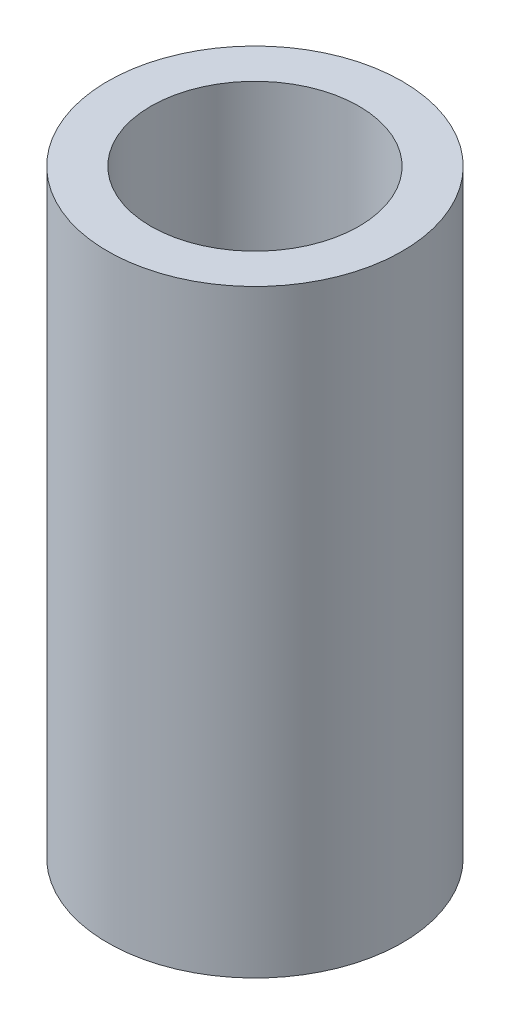
SolidWorks part; units mm, degrees
ref_plane "Front Plane" through (0, 0, 0) normal (0, 0, 1) x (1, 0, 0)
ref_plane "Top Plane" through (0, 0, 0) normal (0, 1, 0) x (1, 0, 0)
ref_plane "Right Plane" through (0, 0, 0) normal (1, 0, 0) x (0, 0, -1)
sketch "Sketch1" plane through (0, 0, 0) normal (0, 1, 0) x (1, 0, 0)
  circle A0 centre (0, 0) radius 7.5
extrude "Boss-Extrude1" add sketch "Sketch1" along normal blind 30.5
sketch "Sketch2" plane through (0, 30.5, 0) normal (0, 1, 0) x (1, 0, 0)
  circle A0 centre (0, 0) radius 5.3
extrude "Cut-Extrude1" cut sketch "Sketch2" against normal through all
